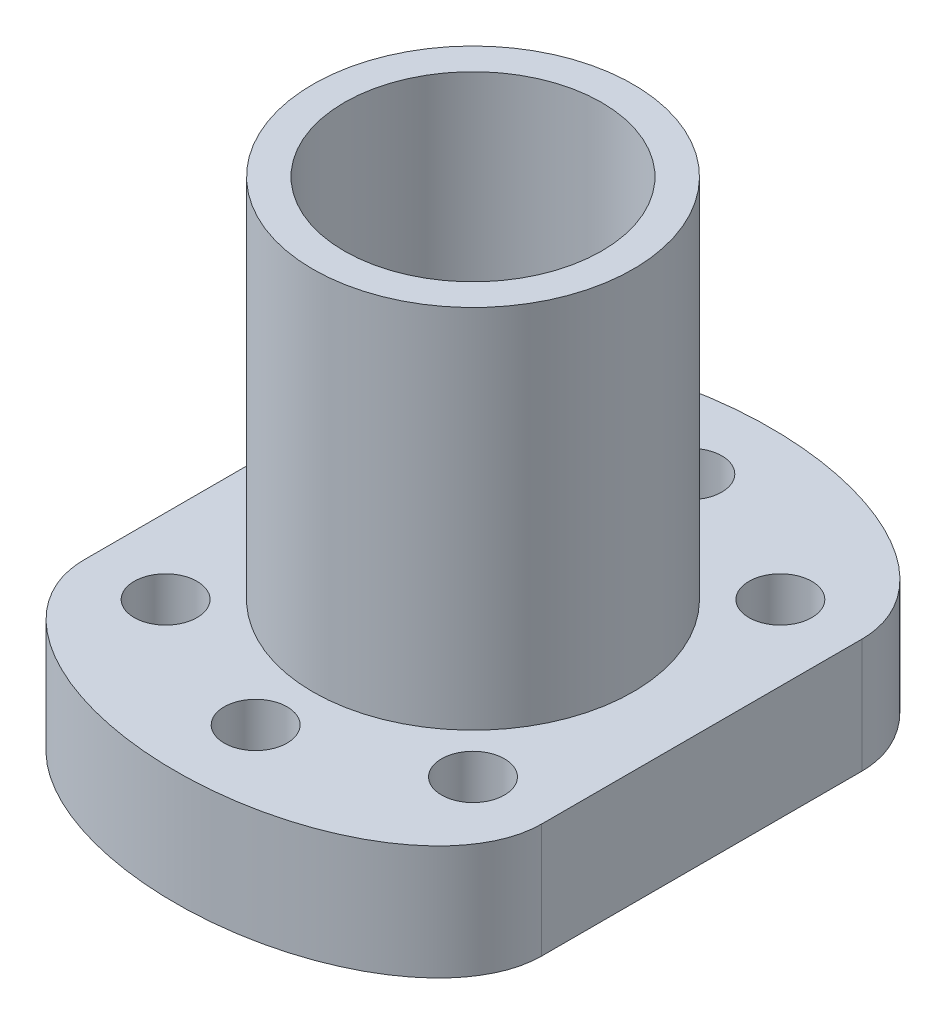
SolidWorks part; units mm, degrees
material "Plain Carbon Steel"
ref_plane "Front Plane" through (0, 0, 0) normal (0, 0, 1) x (1, 0, 0)
ref_plane "Top Plane" through (0, 0, 0) normal (0, 1, 0) x (1, 0, 0)
ref_plane "Right Plane" through (0, 0, 0) normal (1, 0, 0) x (0, 0, -1)
sketch "Sketch1" plane through (0, 0, 0) normal (0, 1, 0) x (1, 0, 0)
  line L0 (0, 26) -> (40, 26) construction
  line L5 (20, 52) -> (20, 0) construction
  line L7 (0, 40) -> (0, 12)
  line L8 (40, 40) -> (40, 12)
  ellipse E0 centre (20, 40) end of major axis (0, 40) minor radius 12 (0, 40) -> (40, 40) cw
  ellipse E1 centre (20, 12) end of major axis (40, 12) minor radius 12 (40, 12) -> (0, 12) cw
extrude "Boss-Extrude1" add sketch "Sketch1" along normal blind 10 contours E0 L8 E1 L7
sketch "Sketch2" plane through (0, 10, 0) normal (0, 1, 0) x (1, 0, 0)
  line L0 (20, 52) -> (20, 0) construction
  circle A0 centre (20, 26) radius 14
  ellipse E0 centre (20, 40) end of major axis (0, 40) minor radius 12 (40, 40) -> (0, 40) ccw construction
  ellipse E1 centre (20, 12) end of major axis (40, 12) minor radius 12 (0, 12) -> (40, 12) ccw construction
  dimension "D1" = 28
extrude "Boss-Extrude2" add sketch "Sketch2" along normal blind 32 contours A0
sketch "Sketch3" plane through (0, 42, 0) normal (0, 1, 0) x (1, 0, 0)
  line L0 (20, 40) -> (20, 12) construction
  circle A0 centre (20, 26) radius 14 construction
  circle A1 centre (20, 26) radius 14 construction
  circle A2 centre (20, 26) radius 11.25
  dimension "D1" = 22.5
extrude "Cut-Extrude1" cut sketch "Sketch3" against normal through all
sketch "Sketch4" plane through (0, 10, 0) normal (0, 1, 0) x (1, 0, 0)
  line L0 (20, 52) -> (20, 0) construction
  line L1 (0, 26) -> (40, 26) construction
  line L2 (0, 40) -> (0, 12) construction
  line L3 (40, 40) -> (40, 12) construction
  line L4 (20, 26) -> (50.5481, 56.5481) construction
  line L5 (20, 26) -> (-9.2961, -3.2961) construction
  line L7 (44.4455, 1.5545) -> (-7.4942, 53.4942) construction
  circle A1 centre (20, 45) radius 2.75
  circle A2 centre (33.435, 39.435) radius 2.75
  circle A3 centre (6.565, 39.435) radius 2.75
  circle A4 centre (20, 7) radius 2.75
  circle A5 centre (33.435, 12.565) radius 2.75
  circle A6 centre (6.565, 12.565) radius 2.75
  ellipse E0 centre (20, 40) end of major axis (0, 40) minor radius 12 (40, 40) -> (0, 40) ccw construction
  ellipse E1 centre (20, 12) end of major axis (40, 12) minor radius 12 (0, 12) -> (40, 12) ccw construction
  dimension "D2" = 5.5
  dimension "D6" = 5.5
  dimension "D7" = 5.5
  dimension "D8" = 5.5
  dimension "D9" = 5.5
  dimension "D10" = 5.5
  dimension "D3" = 45
  dimension "D4" = 45
  dimension "D5" = 45
extrude "Cut-Extrude2" cut sketch "Sketch4" against normal through all
